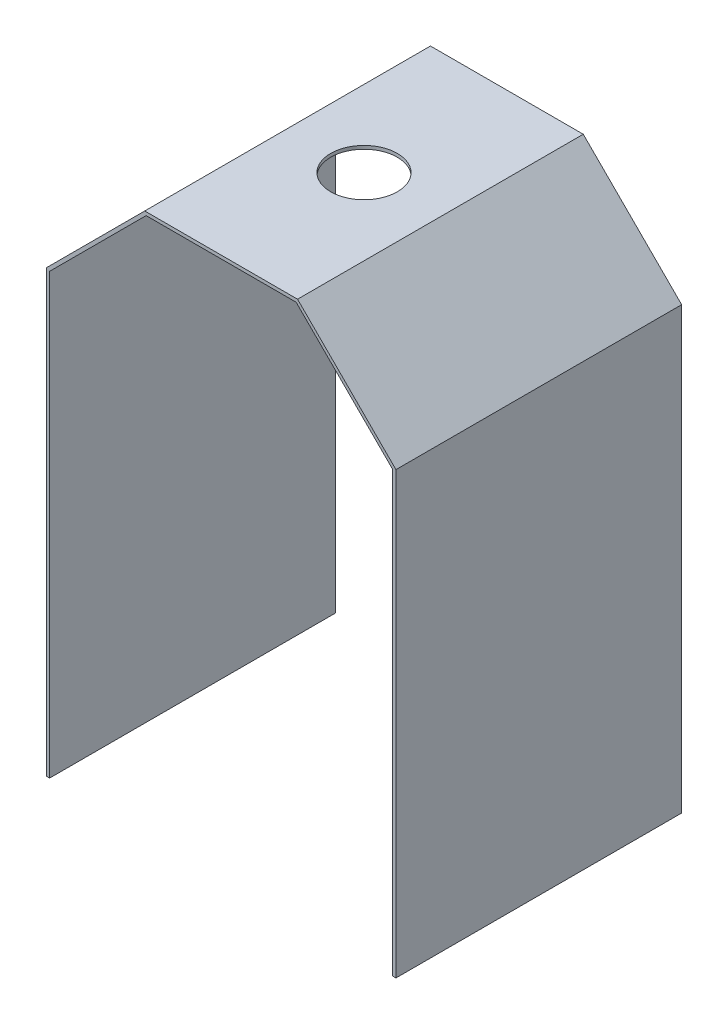
SolidWorks part; units mm, degrees
ref_plane "Спереди" through (0, 0, 0) normal (0, 0, 1) x (1, 0, 0)
ref_plane "Сверху" through (0, 0, 0) normal (0, 1, 0) x (1, 0, 0)
ref_plane "Справа" through (0, 0, 0) normal (1, 0, 0) x (0, 0, -1)
sketch "Эскиз1" plane through (0, 0, 0) normal (0, 0, 1) x (1, 0, 0)
  line L2 (-96.7252, 314.9265) -> (-96.7252, 579.3926)
  line L3 (-96.7252, 579.3926) -> (-37.6214, 638.4965)
  line L4 (-37.6214, 638.4965) -> (54.1709, 638.4965)
  line L5 (54.1709, 638.4965) -> (113.2748, 579.3926)
  line L6 (113.2748, 579.3926) -> (113.2748, 314.9265)
extrude "Вытянуть-Тонкостенный1" add sketch "Эскиз1" along normal blind 171.62 thin
sketch "Эскиз2" plane through (0, 638.4965, 0) normal (0, 1, 0) x (1, 0, 0)
  circle A0 centre (8.2748, -85.81) radius 20
extrude "Вырез-Вытянуть1" cut sketch "Эскиз2" against normal through all
